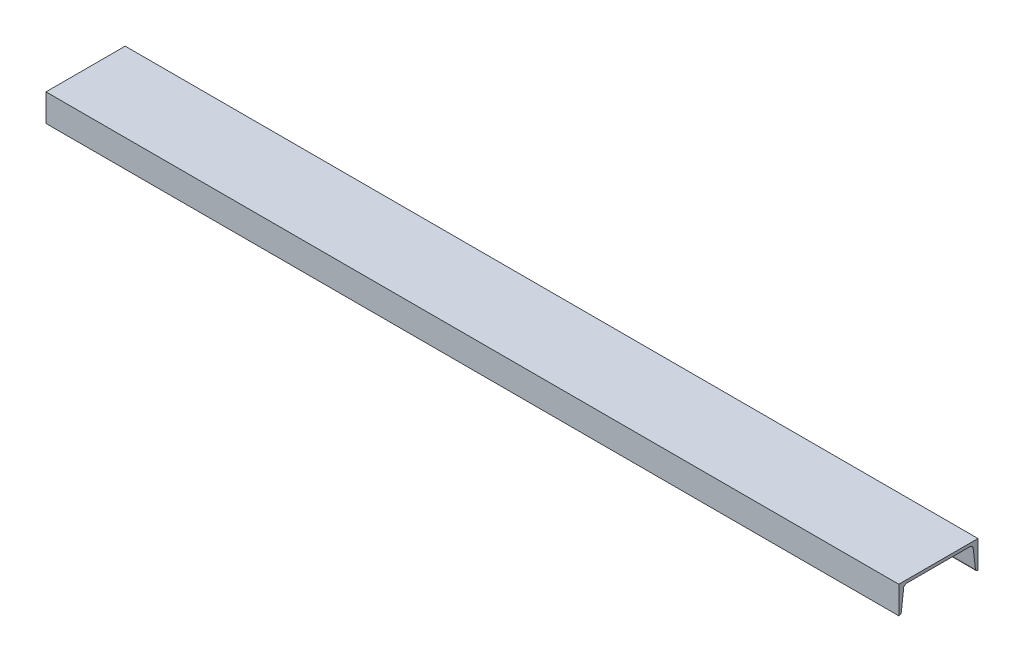
SolidWorks part; units mm, degrees
ref_plane "Спереди" through (0, 0, 0) normal (0, 0, 1) x (1, 0, 0)
ref_plane "Сверху" through (0, 0, 0) normal (0, 1, 0) x (1, 0, 0)
ref_plane "Справа" through (0, 0, 0) normal (1, 0, 0) x (0, 0, -1)
sketch "Эскиз2" plane through (0, 0, 0) normal (1, 0, 0) x (0, 0, -1)
  line L0 (130, 0) -> (-130, 0)
  line L1 (-130, 0) -> (-130, -90)
  line L2 (0, 0) -> (0, -100) construction
  line L3 (101.8373, -10) -> (-101.8373, -10)
  line L4 (-113.796, -16.7206) -> (-121.7267, -83.8216)
  line L5 (-130, -90) -> (-128.6783, -90)
  line L6 (130, -90) -> (128.6783, -90)
  line L7 (113.796, -16.7206) -> (121.7267, -83.8216)
  line L8 (130, 0) -> (130, -90)
  arc A0 (-101.8373, -10) -> (-113.796, -16.7206) centre (-101.8373, -24) ccw
  arc A1 (-128.6783, -90) -> (-121.7267, -83.8216) centre (-128.6783, -83) ccw
  arc A2 (128.6783, -90) -> (121.7267, -83.8216) centre (128.6783, -83) cw
  arc A3 (101.8373, -10) -> (113.796, -16.7206) centre (101.8373, -24) cw
  point P19 (0, -10)
extrude "Бобышка-Вытянуть1" add sketch "Эскиз2" along normal blind 2800
